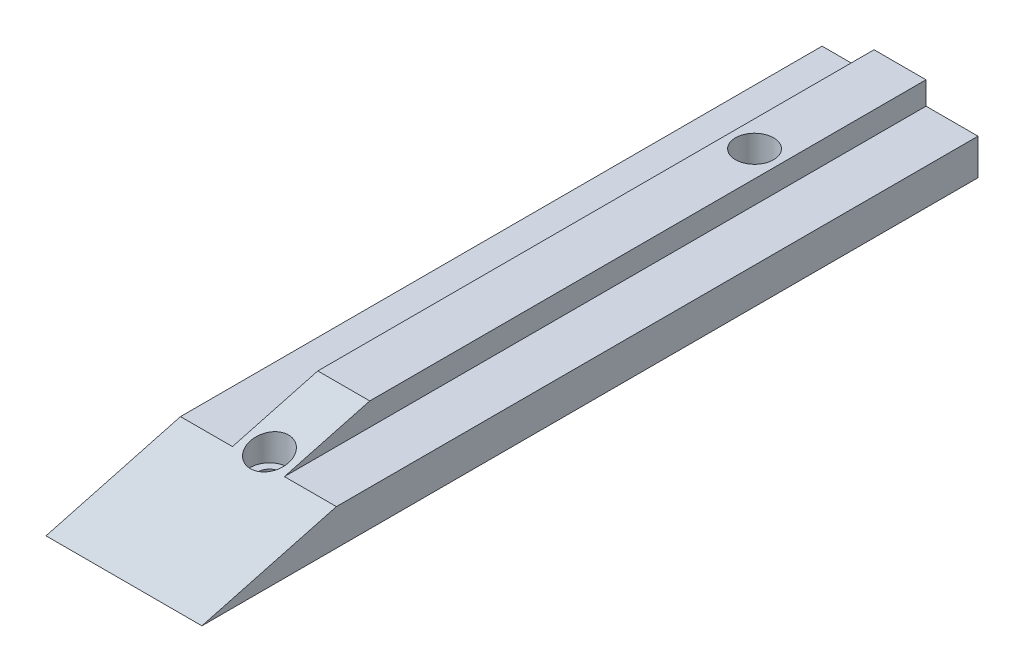
SolidWorks part; units mm, degrees
material "PE1000 Высокой плотности"
ref_plane "Спереди" through (0, 0, 0) normal (0, 0, 1) x (1, 0, 0)
ref_plane "Сверху" through (0, 0, 0) normal (0, 1, 0) x (1, 0, 0)
ref_plane "Справа" through (0, 0, 0) normal (1, 0, 0) x (0, 0, -1)
sketch "Эскиз1" plane through (0, 0, 0) normal (0, 0, 1) x (1, 0, 0)
  line L0 (22.5, 0) -> (-22.5, 0)
  line L1 (-22.5, 0) -> (-22.5, 10.4)
  line L2 (-22.5, 10.4) -> (-7.5, 10.4)
  line L3 (-7.5, 10.4) -> (-7.5, 17)
  line L4 (-7.5, 17) -> (7.5, 17)
  line L5 (0, -55) -> (0, 55) construction
  line L6 (22.5, 0) -> (22.5, 10.4)
  line L7 (22.5, 10.4) -> (7.5, 10.4)
  line L8 (7.5, 10.4) -> (7.5, 17)
  point P10 (0, 0)
  point P13 (0, 17)
  dimension "D1" = 45
  dimension "D2" = 17
  dimension "D3" = 6.6
  dimension "D4" = 15
extrude "Бобышка-Вытянуть1" add sketch "Эскиз1" along normal mid plane 224
sketch "Эскиз5" plane through (22.5, 0, 0) normal (1, 0, 0) x (0, 0, -1)
  line L0 (-112, 0) -> (-48.5551, 17)
  line L1 (-112, 17) -> (112, 17) construction
  line L2 (-48.5551, 17) -> (-112, 17)
  line L3 (-112, 17) -> (-112, 0)
  line L8 (-112, 0) -> (112, 0) construction
  dimension "D1" = 15
extrude "Вырез-Вытянуть2" cut sketch "Эскиз5" against normal through all
sketch "Эскиз7" plane through (0, 17, 0) normal (0, 1, 0) x (1, 0, 0)
  line L0 (0, 112) -> (0, 70) construction
  line L1 (7.5, 112) -> (-7.5, 112) construction
  line L2 (0, 70) -> (0, -70) construction
  line L3 (0, -70) -> (0, -210) construction
  point P7 (0, 70)
  point P8 (0, -70)
  point P16 (0, -210)
  dimension "D1" = 140
  dimension "D2" = 42
hole_wizard "Цековка для винта с внутренним шестигранником M61" positions "Эскиз7" profile "Эскиз8" counterbore size "M6" standard "DIN"
sketch "Эскиз8" plane through (0, 17, 210) normal (1, 0, 0) x (0, 0, 1)
  line L0 (0, 0) -> (0, 21.9828)
  line L1 (0, 21.9828) -> (3.3, 20)
  line L2 (3.3, 20) -> (3.3, 12.4)
  line L3 (3.3, 12.4) -> (5.5, 12.4)
  line L4 (5.5, 12.4) -> (5.5, 0)
  line L5 (5.5, 0) -> (0, 0)
  line L10 (0, 21.9828) -> (-3.3, 20) construction
  line L11 (0, -6.35) -> (0, 107.95) construction
  dimension "Диаметр отверстия" = 6.6
  dimension "Глубина отверстия" = 20
  dimension "Диаметр цековки" = 11
  dimension "Глубина цековки" = 12.4
  dimension "Угол заточки сверла" = 118
move or copy body "Тело-Переместить/Копировать1" [suppressed] bodies to move or copy 105
